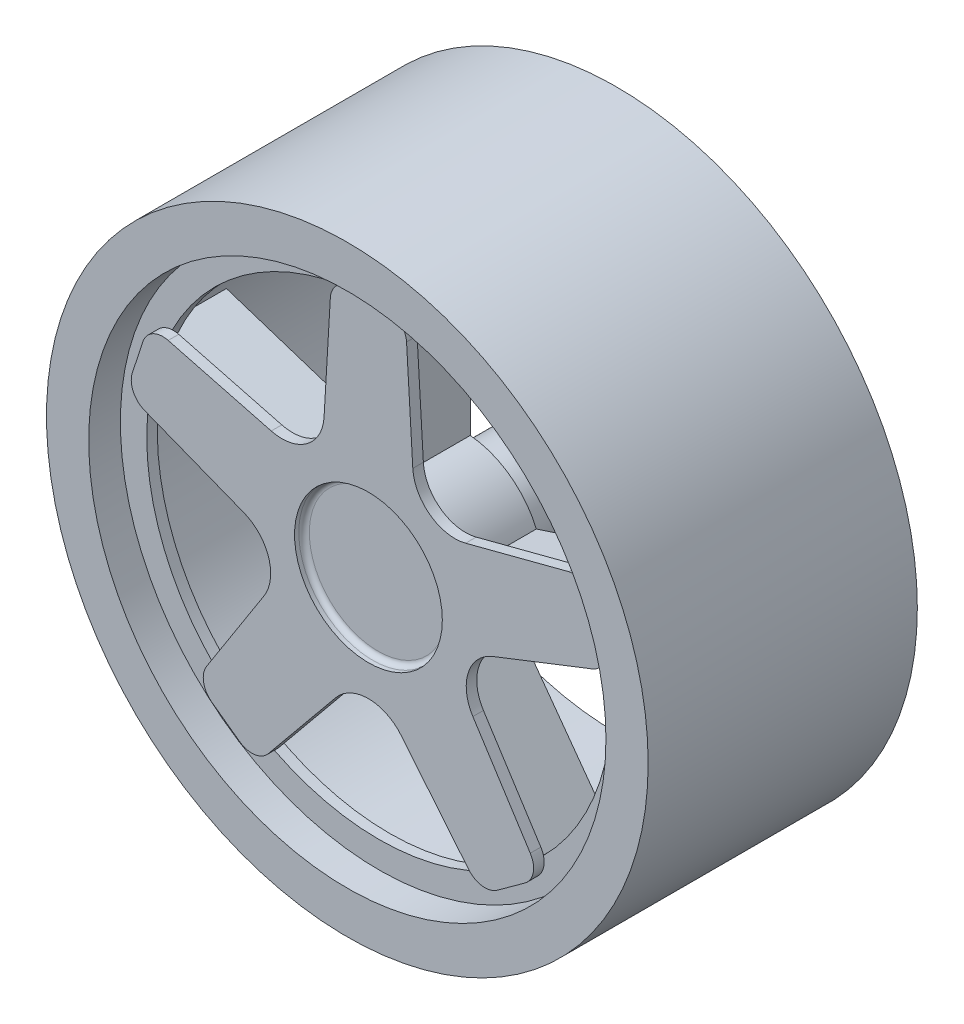
SolidWorks part; units mm, degrees
ref_plane "Front Plane" through (0, 0, 0) normal (0, 0, 1) x (1, 0, 0)
ref_plane "Top Plane" through (0, 0, 0) normal (0, 1, 0) x (1, 0, 0)
ref_plane "Right Plane" through (0, 0, 0) normal (1, 0, 0) x (0, 0, -1)
sketch "Sketch1" plane through (0, 0, 0) normal (0, 0, 1) x (1, 0, 0)
  circle A0 centre (0, 0) radius 22
  circle A1 centre (0, 0) radius 24.5
  point P5 (1.5854, -0.8456)
  point P6 (-0.6342, 0)
  dimension "D1" = 44
  dimension "D2" = 49
extrude "Boss-Extrude1" add sketch "Sketch1" along normal blind 1
sketch "Sketch2" plane through (0, 0, 1) normal (0, 0, 1) x (1, 0, 0)
  line L0 (-1.6142, 23) -> (1.6142, 23)
  line L1 (3.6107, 21.1174) -> (4.2032, 11.0463)
  line L2 (-4.2032, 11.0463) -> (-3.6107, 21.1174)
  line L3 (0, 0) -> (0, 23) construction
  line L4 (-4.5, 6) -> (4.5, 6) construction
  line L5 (0, 6) -> (0, 0) construction
  line L6 (21.3755, 8.6426) -> (22.3731, 5.5722)
  line L7 (21.1997, 3.0916) -> (11.8045, -0.584)
  line L8 (9.2068, 7.4109) -> (18.9681, 9.9597)
  line L9 (4.3158, 6.1339) -> (7.0969, -2.4257) construction
  line L10 (14.825, -17.6586) -> (12.2132, -19.5562)
  line L11 (9.4914, -19.2067) -> (3.0924, -11.4072)
  line L12 (9.8933, -6.4661) -> (15.3337, -14.962)
  line L13 (7.1673, -2.2091) -> (-0.1139, -7.4991) construction
  line L14 (-12.2132, -19.5562) -> (-14.825, -17.6586)
  line L15 (-15.3337, -14.962) -> (-9.8933, -6.4661)
  line L16 (-3.0924, -11.4072) -> (-9.4914, -19.2067)
  line L17 (0.1139, -7.4991) -> (-7.1673, -2.2091) construction
  line L18 (-22.3731, 5.5722) -> (-21.3755, 8.6426)
  line L19 (-18.9681, 9.9597) -> (-9.2068, 7.4109)
  line L20 (-11.8045, -0.584) -> (-21.1997, 3.0916)
  line L21 (-7.0969, -2.4257) -> (-4.3158, 6.1339) construction
  arc A0 (-9.8933, -6.4661) -> (-11.8045, -0.584) centre (-13.2618, -4.309) ccw
  arc A1 (-3.0924, -11.4072) -> (3.0924, -11.4072) centre (0, -13.9443) cw
  arc A2 (9.8933, -6.4661) -> (11.8045, -0.584) centre (13.2618, -4.309) cw
  arc A3 (9.2068, 7.4109) -> (4.2032, 11.0463) centre (8.1963, 11.2812) cw
  arc A4 (-9.2068, 7.4109) -> (-4.2032, 11.0463) centre (-8.1963, 11.2812) ccw
  arc A5 (-1.6142, 23) -> (-3.6107, 21.1174) centre (-1.6142, 21) ccw
  arc A6 (1.6142, 23) -> (3.6107, 21.1174) centre (1.6142, 21) cw
  arc A7 (21.3755, 8.6426) -> (18.9681, 9.9597) centre (19.4734, 8.0245) ccw
  arc A8 (22.3731, 5.5722) -> (21.1997, 3.0916) centre (20.471, 4.9542) cw
  arc A9 (14.825, -17.6586) -> (15.3337, -14.962) centre (13.6494, -16.0406) ccw
  arc A10 (12.2132, -19.5562) -> (9.4914, -19.2067) centre (11.0376, -17.9382) cw
  arc A11 (-12.2132, -19.5562) -> (-9.4914, -19.2067) centre (-11.0376, -17.9382) ccw
  arc A12 (-14.825, -17.6586) -> (-15.3337, -14.962) centre (-13.6494, -16.0406) cw
  arc A13 (-21.3755, 8.6426) -> (-18.9681, 9.9597) centre (-19.4734, 8.0245) cw
  arc A14 (-22.3731, 5.5722) -> (-21.1997, 3.0916) centre (-20.471, 4.9542) ccw
  point P27 (0, 0)
  point P42 (-3.5, 23)
  point P45 (3.5, 23)
  dimension "D6" = 4
  dimension "D7" = 2
  dimension "D1" = 7
  dimension "D2" = 9
  dimension "D3" = 17
  dimension "D4" = 23
  dimension "D5" = 5
extrude "Boss-Extrude2" add sketch "Sketch2" along normal blind 1
sketch "Sketch3" plane through (0, 0, 2) normal (0, 0, 1) x (1, 0, 0)
  circle A0 centre (0, 0) radius 7
extrude "Cut-Extrude1" cut sketch "Sketch3" against normal blind 0.9
fillet "Fillet1" radius 0.5 1 edges at (7, 0, 1.1)
sketch "Sketch4" plane through (0, 0, 0) normal (0, 0, 1) x (1, 0, 0)
  circle A0 centre (0, 0) radius 24.5
  circle A2 centre (0, 0) radius 28.5
  dimension "D1" = 49
  dimension "D2" = 4
extrude "Boss-Extrude3" add sketch "Sketch4" along normal blind 4 and the other way blind 21.5
sketch "Sketch5" plane through (0, 0, 1) normal (0, 0, -1) x (-1, 0, 0)
  line L0 (22.4518, 7.9754) -> (22.8517, 6.7446)
  line L1 (-0.6471, 23.8175) -> (0.6471, 23.8175)
  line L2 (-0.6471, 23.8175) -> (-0.6471, 7.472)
  line L4 (0.6471, 23.8175) -> (0.6471, 7.472)
  line L5 (-0.6471, 23.8175) -> (0.5558, 7.4794) construction
  line L6 (-0.5558, 7.4794) -> (0.6471, 23.8175) construction
  line L7 (22.4518, 7.9754) -> (6.9064, 2.9244)
  line L9 (22.8517, 6.7446) -> (7.3063, 1.6936)
  line L10 (22.4518, 7.9754) -> (7.2851, 1.7826) construction
  line L11 (6.9415, 2.8399) -> (22.8517, 6.7446) construction
  line L12 (14.523, -18.8884) -> (13.4761, -19.6491)
  line L13 (14.523, -18.8884) -> (4.9154, -5.6647)
  line L15 (13.4761, -19.6491) -> (3.8685, -6.4253)
  line L16 (14.523, -18.8884) -> (3.9466, -6.3777) construction
  line L17 (4.8459, -5.7242) -> (13.4761, -19.6491) construction
  line L18 (-13.4761, -19.6491) -> (-14.523, -18.8884)
  line L19 (-13.4761, -19.6491) -> (-3.8685, -6.4253)
  line L21 (-14.523, -18.8884) -> (-4.9154, -5.6647)
  line L22 (-13.4761, -19.6491) -> (-4.8459, -5.7242) construction
  line L23 (-3.9466, -6.3777) -> (-14.523, -18.8884) construction
  line L24 (-22.8517, 6.7446) -> (-22.4518, 7.9754)
  line L25 (-22.8517, 6.7446) -> (-7.3063, 1.6936)
  line L27 (-22.4518, 7.9754) -> (-6.9064, 2.9244)
  line L28 (-22.8517, 6.7446) -> (-6.9415, 2.8399) construction
  line L29 (-7.2851, 1.7826) -> (-22.4518, 7.9754) construction
  arc A0 (-0.6471, 7.472) -> (-6.9064, 2.9244) centre (0, 0) ccw
  arc A1 (6.9064, 2.9244) -> (0.6471, 7.472) centre (0, 0) ccw
  arc A2 (-7.3063, 1.6936) -> (-4.9154, -5.6647) centre (0, 0) ccw
  arc A3 (4.9154, -5.6647) -> (7.3063, 1.6936) centre (0, 0) ccw
  arc A4 (-3.8685, -6.4253) -> (3.8685, -6.4253) centre (0, 0) ccw
  point P3 (0, 15.0289)
  point P11 (14.2933, 4.6442)
  point P16 (8.8338, -12.1586)
  point P21 (-8.8338, -12.1586)
  point P26 (-14.2933, 4.6442)
  point P31 (0, 0)
  dimension "D1" = 15
  dimension "D2" = 5
extrude "Boss-Extrude4" add sketch "Sketch5" along normal blind 8
sketch "Sketch6" plane through (0, 0, -7) normal (0, 0, -1) x (-1, 0, 0)
  line L1 (-2.4367, -1.75) -> (2.4367, -1.75)
  line L3 (-2.4367, 1.75) -> (2.4367, 1.75)
  line L5 (-2.4367, -1.75) -> (2.4367, 1.75) construction
  line L6 (-2.4367, 1.75) -> (2.4367, -1.75) construction
  circle A0 centre (0, 0) radius 4.6
  arc A1 (-2.4367, 1.75) -> (-2.4367, -1.75) centre (0, 0) ccw
  arc A2 (2.4367, -1.75) -> (2.4367, 1.75) centre (0, 0) ccw
  dimension "D1" = 9.2
  dimension "D3" = 6
  dimension "D2" = 3.5
extrude "Boss-Extrude5" add sketch "Sketch6" along normal blind 17.5
